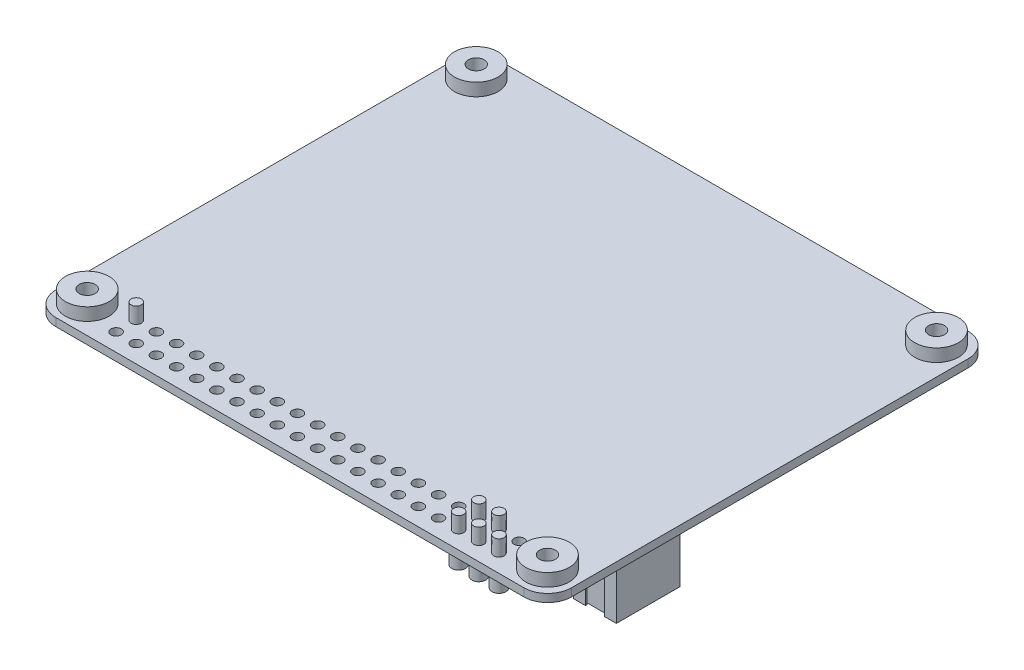
SolidWorks part; units mm, degrees
ref_plane "前视基准面" through (0, 0, 0) normal (0, 0, 1) x (1, 0, 0)
ref_plane "上视基准面" through (0, 0, 0) normal (0, 1, 0) x (1, 0, 0)
ref_plane "右视基准面" through (0, 0, 0) normal (1, 0, 0) x (0, 0, -1)
sketch "草图1" plane through (0, 0, 0) normal (0, 1, 0) x (1, 0, 0)
  line L1 (32.5, -28) -> (-32.5, -28)
  line L2 (32.5, -28) -> (32.5, 28)
  line L3 (32.5, 28) -> (-32.5, 28)
  line L4 (-32.5, -28) -> (-32.5, 28)
  line L5 (32.5, -28) -> (-32.5, 28) construction
  line L6 (32.5, 28) -> (-32.5, -28) construction
  point P0 (0, 0)
  dimension "D1" = 56
  dimension "D2" = 65
extrude "凸台-拉伸1" add sketch "草图1" along normal blind 1
fillet "圆角1" radius 3 4 edges at (32.5, 0.5, -28) (32.5, 0.5, 28) (-32.5, 0.5, 28) (-32.5, 0.5, -28)
sketch "草图2" plane through (0, 1, 0) normal (0, 1, 0) x (1, 0, 0)
  circle A0 centre (-29.0307, 24.5287) radius 2.75
  circle A1 centre (28.9808, 24.5287) radius 2.75
  circle A2 centre (-29.0307, -24.5065) radius 2.75
  circle A3 centre (28.9808, -24.5065) radius 2.75
  dimension "D1" = 5.5
extrude "凸台-拉伸2" add sketch "草图2" along normal blind 1.6
sketch "草图3" plane through (0, 2.6, 0) normal (0, 1, 0) x (1, 0, 0)
  circle A0 centre (-29.0307, 24.5287) radius 1
  circle A1 centre (28.9808, 24.5287) radius 1
  circle A2 centre (-29.0307, -24.5065) radius 1
  circle A3 centre (28.9808, -24.5065) radius 1
  dimension "D1" = 2
extrude "切除-拉伸1" cut sketch "草图3" against normal up to next
sketch "草图4" plane through (0, 0, 0) normal (0, -1, 0) x (1, 0, 0)
  line L0 (29.5, -28) -> (-29.5, -28) construction
  line L1 (25.5, -28) -> (16.5, -28)
  line L2 (25.5, -28) -> (25.5, -20.6)
  line L3 (25.5, -20.6) -> (16.5, -20.6)
  line L4 (16.5, -28) -> (16.5, -20.6)
  line L5 (32.5, 25) -> (32.5, -25) construction
  dimension "D1" = 7.4
  dimension "D2" = 9
  dimension "D3" = 7
extrude "凸台-拉伸3" add sketch "草图4" along normal blind 3.2
sketch "草图5" plane through (0, 0, -28) normal (0, 0, -1) x (-1, 0, 0)
  line L0 (-29.5, 0) -> (-25.5, 0) construction
  line L1 (-16.5, -3.2) -> (-25.5, -3.2)
  line L2 (-16.5, -3.2) -> (-16.5, 0)
  line L3 (-16.5, 0) -> (-25.5, 0)
  line L4 (-25.5, -3.2) -> (-25.5, 0)
  line L5 (-25.5, -3.2) -> (-25.5, 0) construction
extrude "凸台-拉伸4" add sketch "草图5" along normal blind 1
fillet "圆角3" radius 1 4 edges at (25.5, 0, -28.5) (25.5, -3.2, -24.8) (16.5, -3.2, -24.8) (16.5, 0, -28.5)
sketch "草图6" plane through (0, 0, 0) normal (0, -1, 0) x (1, 0, 0)
  line L0 (-32.5, -25) -> (-32.5, 25) construction
  circle A0 centre (-17.5, 0) radius 7
  dimension "D1" = 14
  dimension "D2" = 15
extrude "凸台-拉伸5" add sketch "草图6" along normal blind 2
sketch "草图8" plane through (0, 0, 0) normal (0, -1, 0) x (1, 0, 0)
  circle A0 centre (28.9808, 24.5065) radius 2
  circle A1 centre (28.9808, -24.5287) radius 2
  circle A2 centre (-29.0307, -24.5287) radius 2
  circle A3 centre (-29.0307, 24.5065) radius 2
  dimension "D1" = 4
extrude "凸台-拉伸6" add sketch "草图8" along normal blind 0.5
sketch "草图9" plane through (0, 0, 0) normal (0, 1, 0) x (1, 0, 0)
  circle A0 centre (-29.0307, 24.5287) radius 1
  circle A1 centre (28.9808, 24.5287) radius 1
  circle A2 centre (-29.0307, -24.5065) radius 1
  circle A3 centre (28.9808, -24.5065) radius 1
  circle A4 centre (28.9808, -24.5065) radius 2 construction
  circle A5 centre (28.9808, 24.5287) radius 2 construction
  circle A6 centre (-29.0307, -24.5065) radius 2 construction
  circle A7 centre (-29.0307, 24.5287) radius 2 construction
extrude "切除-拉伸2" cut sketch "草图9" against normal up to next
sketch "草图10" plane through (0, 0, -29) normal (0, 0, -1) x (-1, 0, 0)
  line L8 (-17.5, -0.2) -> (-24.5, -0.2)
  line L9 (-25.3, -1) -> (-25.3, -2.2)
  line L10 (-24.5, -3) -> (-17.5, -3)
  line L11 (-16.7, -2.2) -> (-16.7, -1)
  line L12 (-17.5, -0.2) -> (-24.5, -0.2)
  line L13 (-25.3, -1) -> (-25.3, -2.2)
  line L14 (-24.5, -3) -> (-17.5, -3)
  line L15 (-16.7, -2.2) -> (-16.7, -1)
  arc A8 (-24.5, -0.2) -> (-25.3, -1) centre (-24.5, -1) ccw
  arc A9 (-25.3, -2.2) -> (-24.5, -3) centre (-24.5, -2.2) ccw
  arc A10 (-17.5, -3) -> (-16.7, -2.2) centre (-17.5, -2.2) ccw
  arc A11 (-16.7, -1) -> (-17.5, -0.2) centre (-17.5, -1) ccw
  arc A12 (-24.5, -0.2) -> (-25.3, -1) centre (-24.5, -1) ccw
  arc A13 (-25.3, -2.2) -> (-24.5, -3) centre (-24.5, -2.2) ccw
  arc A14 (-17.5, -3) -> (-16.7, -2.2) centre (-17.5, -2.2) ccw
  arc A15 (-16.7, -1) -> (-17.5, -0.2) centre (-17.5, -1) ccw
  dimension "D1" = 0.2
extrude "切除-拉伸3" cut sketch "草图10" against normal blind 8
sketch "草图11" plane through (0, 0, 0) normal (0, -1, 0) x (1, 0, 0)
  line L0 (16.5, -28) -> (-29.5, -28) construction
  line L1 (6, -27.8) -> (10.5, -27.8)
  line L2 (6, -27.8) -> (6, -26.3)
  line L3 (6, -26.3) -> (10.5, -26.3)
  line L4 (10.5, -27.8) -> (10.5, -26.3)
  line L5 (16.5, -20.6) -> (16.5, -28) construction
  line L6 (-2.6793, -27.2) -> (-9.3793, -27.2)
  line L7 (-2.6793, -27.2) -> (-2.6793, -25)
  line L8 (-2.6793, -25) -> (-9.3793, -25)
  line L9 (-9.3793, -27.2) -> (-9.3793, -25)
  point P4 (0, 0)
  dimension "D1" = 6
  dimension "D2" = 4.5
  dimension "D3" = 6.7
  dimension "D4" = 0.8
  dimension "D5" = 2.2
  dimension "D6" = 1.5
  dimension "D7" = 8.7
  dimension "D8" = 0.2
extrude "凸台-拉伸7" add sketch "草图11" along normal blind 1.5
sketch "草图12" plane through (0, 0, 0) normal (0, -1, 0) x (1, 0, 0)
  line L0 (16.5, -28) -> (-29.5, -28) construction
  line L1 (-16.6, -28) -> (-23.9, -28)
  line L2 (-16.6, -28) -> (-16.6, -22.7)
  line L3 (-16.6, -22.7) -> (-23.9, -22.7)
  line L4 (-23.9, -28) -> (-23.9, -22.7)
  line L5 (-32.5, -25) -> (-32.5, 25) construction
  dimension "D1" = 7.3
  dimension "D2" = 8.6
  dimension "D3" = 5.3
extrude "凸台-拉伸8" add sketch "草图12" along normal blind 2.4
sketch "草图13" plane through (0, 0, -28) normal (0, 0, -1) x (-1, 0, 0)
  line L1 (23.9, -2.4) -> (16.6, -2.4)
  line L2 (23.9, -2.4) -> (23.9, 0)
  line L3 (23.9, 0) -> (16.6, 0)
  line L4 (16.6, -2.4) -> (16.6, 0)
extrude "凸台-拉伸9" add sketch "草图13" along normal up to surface (1 mm away) up to face at (21, -1.6, -29)
chamfer "倒角1" distance 0.4 angle 45 2 edges at (-16.6, -2.4, -25.85) (-23.9, -2.4, -25.85)
chamfer "倒角2" distance 1 angle 45 2 edges at (-16.6, 0, -28.5) (-23.9, 0, -28.5)
sketch "草图14" plane through (0, 0, -29) normal (0, 0, -1) x (-1, 0, 0)
  line L16 (22.8172, -0.2) -> (17.6828, -0.2)
  line L17 (17.6828, -0.2) -> (16.8, -1.0828)
  line L18 (16.8, -1.0828) -> (16.8, -1.9172)
  line L19 (16.8, -1.9172) -> (17.0828, -2.2)
  line L20 (17.0828, -2.2) -> (23.4172, -2.2)
  line L21 (23.4172, -2.2) -> (23.7, -1.9172)
  line L22 (23.7, -1.9172) -> (23.7, -1.0828)
  line L23 (23.7, -1.0828) -> (22.8172, -0.2)
  line L24 (22.8172, -0.2) -> (17.6828, -0.2)
  line L25 (17.6828, -0.2) -> (16.8, -1.0828)
  line L26 (16.8, -1.0828) -> (16.8, -1.9172)
  line L27 (16.8, -1.9172) -> (17.0828, -2.2)
  line L28 (17.0828, -2.2) -> (23.4172, -2.2)
  line L29 (23.4172, -2.2) -> (23.7, -1.9172)
  line L30 (23.7, -1.9172) -> (23.7, -1.0828)
  line L31 (23.7, -1.0828) -> (22.8172, -0.2)
  dimension "D1" = 0.2
extrude "切除-拉伸4" cut sketch "草图14" against normal blind 2.4
sketch "草图15" plane through (0, 0, -27.2) normal (0, 0, -1) x (-1, 0, 0)
  line L1 (6.6577, -1.3336) -> (5.7436, -1.3336)
  line L2 (6.6577, -1.3336) -> (6.6577, -0.2043)
  line L3 (6.6577, -0.2043) -> (5.7436, -0.2043)
  line L4 (5.7436, -1.3336) -> (5.7436, -0.2043)
extrude "凸台-拉伸10" add sketch "草图15" along normal blind 0.8
sketch "草图16" plane through (0, 0, -27.8) normal (0, 0, -1) x (-1, 0, 0)
  line L1 (-6.8432, -1.3088) -> (-8.9595, -1.3088)
  line L2 (-6.8432, -1.3088) -> (-6.8432, -0.1641)
  line L3 (-6.8432, -0.1641) -> (-8.9595, -0.1641)
  line L4 (-8.9595, -1.3088) -> (-8.9595, -0.1641)
extrude "凸台-拉伸11" add sketch "草图16" along normal blind 0.5
sketch "草图17" plane through (0, 0, -28) normal (0, 0, -1) x (-1, 0, 0)
  line L0 (23.9, -1) -> (23.9, 0)
  line L1 (23.9, 0) -> (22.9, 0)
  line L2 (22.9, 0) -> (23.9, -1)
  line L3 (16.6, 0) -> (17.6, 0)
  line L4 (17.6, 0) -> (16.6, -1)
  line L5 (16.6, -1) -> (16.6, 0) construction
  line L6 (16.6, -1) -> (16.6, 0)
extrude "切除-拉伸5" cut sketch "草图17" against normal up to surface (5.3 mm away) up to face at (-20.25, -1.4667, -22.7)
fillet "圆角4" radius 0.2 1 edges at (-17.5, -2, -7)
sketch "草图18" plane through (0, 0, 0) normal (0, -1, 0) x (1, 0, 0)
  line L0 (-29.5, 28) -> (29.5, 28) construction
  line L1 (27.1, 8.3) -> (20.1, 8.3)
  line L2 (27.1, 8.3) -> (27.1, 1.3)
  line L3 (27.1, 1.3) -> (20.1, 1.3)
  line L4 (20.1, 8.3) -> (20.1, 1.3)
  line L5 (27.1, -3.4) -> (20.1, -3.4)
  line L6 (27.1, -3.4) -> (27.1, -10.4)
  line L7 (27.1, -10.4) -> (20.1, -10.4)
  line L8 (20.1, -3.4) -> (20.1, -10.4)
  line L9 (32.5, 25) -> (32.5, -25) construction
  dimension "D1" = 7
  dimension "D2" = 19.7
  dimension "D3" = 4.7
  dimension "D4" = 5.4
extrude "凸台-拉伸12" add sketch "草图18" along normal blind 3
sketch "草图19" plane through (0, 0, 0) normal (0, -1, 0) x (1, 0, 0)
  line L0 (32.5, 25) -> (32.5, -25) construction
  line L1 (32, 18.85) -> (26.6, 18.85)
  line L2 (32, 18.85) -> (32, 10.85)
  line L3 (32, 10.85) -> (26.6, 10.85)
  line L4 (26.6, 18.85) -> (26.6, 10.85)
  line L5 (-29.5, 28) -> (29.5, 28) construction
  dimension "D1" = 8
  dimension "D2" = 5.4
  dimension "D3" = 0.5
  dimension "D4" = 9.15
extrude "凸台-拉伸13" add sketch "草图19" along normal blind 6.22
sketch "草图20" plane through (0, -6.22, 0) normal (0, -1, 0) x (1, 0, 0)
  line L0 (30.5, 18.85) -> (30.5, 18.65)
  line L1 (32, 18.85) -> (26.6, 18.85) construction
  line L2 (30.5, 18.65) -> (31.3599, 18.65)
  line L3 (31.3599, 18.65) -> (31.3599, 18.45)
  line L4 (31.3599, 18.45) -> (26.9378, 18.45)
  line L5 (26.9378, 18.45) -> (26.9378, 18.65)
  line L6 (26.9378, 18.65) -> (28.1, 18.65)
  line L7 (28.1, 18.65) -> (28.1, 18.85)
  line L8 (32, 18.85) -> (26.6, 18.85) construction
  line L9 (28.1, 18.85) -> (30.5, 18.85)
  line L10 (30.5, 10.85) -> (30.5, 11.05)
  line L11 (26.6, 10.85) -> (32, 10.85) construction
  line L12 (30.5, 11.05) -> (31.3599, 11.05)
  line L13 (31.3599, 11.05) -> (31.3599, 11.25)
  line L14 (31.3599, 11.25) -> (26.9378, 11.25)
  line L15 (26.9378, 11.25) -> (26.9378, 11.05)
  line L16 (26.9378, 11.05) -> (28.1, 11.05)
  line L17 (28.1, 11.05) -> (28.1, 10.85)
  line L18 (28.1, 10.85) -> (30.5, 10.85)
  line L19 (32, 10.85) -> (32, 18.85) construction
  line L20 (26.6, 18.85) -> (26.6, 10.85) construction
  dimension "D1" = 0.2
  dimension "D2" = 0.2
  dimension "D3" = 0.2
  dimension "D4" = 1.5
  dimension "D5" = 1.5
extrude "切除-拉伸6" cut sketch "草图20" against normal blind 6.22
sketch "草图21" plane through (0, -6.22, 0) normal (0, -1, 0) x (1, 0, 0)
  line L1 (31.3599, 18.0753) -> (26.9378, 18.0753)
  line L2 (31.3599, 18.0753) -> (31.3599, 11.6247)
  line L3 (31.3599, 11.6247) -> (26.9378, 11.6247)
  line L4 (26.9378, 18.0753) -> (26.9378, 11.6247)
  line L5 (31.3599, 18.0753) -> (26.9378, 11.6247) construction
  line L6 (31.3599, 11.6247) -> (26.9378, 18.0753) construction
  point P0 (29.1489, 14.85)
extrude "切除-拉伸7" cut sketch "草图21" against normal blind 5
sketch "草图22" plane through (0, -1.22, 0) normal (0, -1, 0) x (1, 0, 0)
  line L1 (29.5742, 16.0721) -> (29.0742, 16.0721)
  line L2 (29.5742, 16.0721) -> (29.5742, 15.5721)
  line L3 (29.5742, 15.5721) -> (29.0742, 15.5721)
  line L4 (29.0742, 16.0721) -> (29.0742, 15.5721)
  line L5 (29.5742, 16.0721) -> (29.0742, 15.5721) construction
  line L6 (29.5742, 15.5721) -> (29.0742, 16.0721) construction
  line L7 (29.5566, 14.331) -> (29.0566, 14.331)
  line L8 (29.5566, 14.331) -> (29.5566, 13.831)
  line L9 (29.5566, 13.831) -> (29.0566, 13.831)
  line L10 (29.0566, 14.331) -> (29.0566, 13.831)
  line L11 (29.5566, 14.331) -> (29.0566, 13.831) construction
  line L12 (29.5566, 13.831) -> (29.0566, 14.331) construction
  point P0 (29.3242, 15.8221)
  point P5 (29.3066, 14.081)
  dimension "D1" = 0.5
extrude "凸台-拉伸14" add sketch "草图22" along normal blind 5
chamfer "倒角3" distance 0.1 angle 45 8 edges at (29.3066, -6.22, 14.331) (29.5566, -6.22, 14.081) (29.3066, -6.22, 13.831) (29.0566, -6.22, 14.081) (29.3242, -6.22, 16.0721) (29.5742, -6.22, 15.8221) (29.3242, -6.22, 15.5721) (29.0742, -6.22, 15.8221)
sketch "草图23" plane through (0, 0, 0) normal (0, -1, 0) x (1, 0, 0)
  circle A0 centre (12.8757, -15.76) radius 3.3198
extrude "凸台-拉伸15" add sketch "草图23" along normal blind 1.5
sketch "草图24" plane through (0, 0, 0) normal (0, -1, 0) x (1, 0, 0)
  line L1 (18.7716, 11.9855) -> (16.6907, 11.9855)
  line L2 (18.7716, 11.9855) -> (18.7716, 7.4768)
  line L3 (18.7716, 7.4768) -> (16.6907, 7.4768)
  line L4 (16.6907, 11.9855) -> (16.6907, 7.4768)
  line L5 (18.7716, 11.9855) -> (16.6907, 7.4768) construction
  line L6 (18.7716, 7.4768) -> (16.6907, 11.9855) construction
  line L7 (18.7716, 5.3092) -> (16.6907, 5.3092)
  line L8 (18.7716, 5.3092) -> (18.7716, 0.974)
  line L9 (18.7716, 0.974) -> (16.6907, 0.974)
  line L10 (16.6907, 5.3092) -> (16.6907, 0.974)
  line L11 (18.7716, 5.3092) -> (16.6907, 0.974) construction
  line L12 (18.7716, 0.974) -> (16.6907, 5.3092) construction
  line L13 (15.6772, -1.762) -> (10.6483, -1.762)
  line L14 (15.6772, -1.762) -> (15.6772, -7.762)
  line L15 (15.6772, -7.762) -> (10.6483, -7.762)
  line L16 (10.6483, -1.762) -> (10.6483, -7.762)
  line L17 (15.6772, -1.762) -> (10.6483, -7.762) construction
  line L18 (15.6772, -7.762) -> (10.6483, -1.762) construction
  point P0 (17.7311, 9.7312)
  point P5 (17.7311, 3.1416)
  point P10 (13.1628, -4.762)
  dimension "D1" = 6
extrude "凸台-拉伸16" add sketch "草图24" along normal blind 1.5
sketch "草图25" plane through (0, 0, 0) normal (0, -1, 0) x (1, 0, 0)
  line L1 (15.1967, 7.9079) -> (11.1314, 7.9079)
  line L2 (15.1967, 7.9079) -> (15.1967, 3.8427)
  line L3 (15.1967, 3.8427) -> (11.1314, 3.8427)
  line L4 (11.1314, 7.9079) -> (11.1314, 3.8427)
  line L5 (15.1967, 7.9079) -> (11.1314, 3.8427) construction
  line L6 (15.1967, 3.8427) -> (11.1314, 7.9079) construction
  line L7 (21.5006, 15.4932) -> (19.7006, 15.4932)
  line L8 (21.5006, 15.4932) -> (21.5006, 14.4025)
  line L9 (21.5006, 14.4025) -> (19.7006, 14.4025)
  line L10 (19.7006, 15.4932) -> (19.7006, 14.4025)
  line L11 (21.5006, 15.4932) -> (19.7006, 14.4025) construction
  line L12 (21.5006, 14.4025) -> (19.7006, 15.4932) construction
  line L13 (21.5006, 13.6588) -> (19.7006, 13.6588)
  line L14 (21.5006, 13.6588) -> (21.5006, 12.5682)
  line L15 (21.5006, 12.5682) -> (19.7006, 12.5682)
  line L16 (19.7006, 13.6588) -> (19.7006, 12.5682)
  line L17 (21.5006, 13.6588) -> (19.7006, 12.5682) construction
  line L18 (21.5006, 12.5682) -> (19.7006, 13.6588) construction
  line L19 (21.5006, 11.8741) -> (19.7006, 11.8741)
  line L20 (21.5006, 11.8741) -> (21.5006, 10.7834)
  line L21 (21.5006, 10.7834) -> (19.7006, 10.7834)
  line L22 (19.7006, 11.8741) -> (19.7006, 10.7834)
  line L23 (21.5006, 11.8741) -> (19.7006, 10.7834) construction
  line L24 (21.5006, 10.7834) -> (19.7006, 11.8741) construction
  line L25 (18.7662, 14.8563) -> (17.6756, 14.8563)
  line L26 (18.7662, 14.8563) -> (18.7662, 13.0563)
  line L27 (18.7662, 13.0563) -> (17.6756, 13.0563)
  line L28 (17.6756, 14.8563) -> (17.6756, 13.0563)
  line L29 (18.7662, 14.8563) -> (17.6756, 13.0563) construction
  line L30 (18.7662, 13.0563) -> (17.6756, 14.8563) construction
  line L31 (16.9319, 14.8563) -> (15.8412, 14.8563)
  line L32 (16.9319, 14.8563) -> (16.9319, 13.0563)
  line L33 (16.9319, 13.0563) -> (15.8412, 13.0563)
  line L34 (15.8412, 14.8563) -> (15.8412, 13.0563)
  line L35 (16.9319, 14.8563) -> (15.8412, 13.0563) construction
  line L36 (16.9319, 13.0563) -> (15.8412, 14.8563) construction
  line L37 (15.0976, 14.8563) -> (14.0069, 14.8563)
  line L38 (15.0976, 14.8563) -> (15.0976, 13.0563)
  line L39 (15.0976, 13.0563) -> (14.0069, 13.0563)
  line L40 (14.0069, 14.8563) -> (14.0069, 13.0563)
  line L41 (15.0976, 14.8563) -> (14.0069, 13.0563) construction
  line L42 (15.0976, 13.0563) -> (14.0069, 14.8563) construction
  line L43 (13.2632, 14.8563) -> (12.1725, 14.8563)
  line L44 (13.2632, 14.8563) -> (13.2632, 13.0563)
  line L45 (13.2632, 13.0563) -> (12.1725, 13.0563)
  line L46 (12.1725, 14.8563) -> (12.1725, 13.0563)
  line L47 (13.2632, 14.8563) -> (12.1725, 13.0563) construction
  line L48 (13.2632, 13.0563) -> (12.1725, 14.8563) construction
  line L49 (11.3297, 14.8563) -> (10.2391, 14.8563)
  line L50 (11.3297, 14.8563) -> (11.3297, 13.0563)
  line L51 (11.3297, 13.0563) -> (10.2391, 13.0563)
  line L52 (10.2391, 14.8563) -> (10.2391, 13.0563)
  line L53 (11.3297, 14.8563) -> (10.2391, 13.0563) construction
  line L54 (11.3297, 13.0563) -> (10.2391, 14.8563) construction
  line L55 (9.2971, 14.8563) -> (8.2064, 14.8563)
  line L56 (9.2971, 14.8563) -> (9.2971, 13.0563)
  line L57 (9.2971, 13.0563) -> (8.2064, 13.0563)
  line L58 (8.2064, 14.8563) -> (8.2064, 13.0563)
  line L59 (9.2971, 14.8563) -> (8.2064, 13.0563) construction
  line L60 (9.2971, 13.0563) -> (8.2064, 14.8563) construction
  point P0 (13.1641, 5.8753)
  point P5 (20.6006, 14.9478)
  point P10 (20.6006, 13.1135)
  point P15 (20.6006, 11.3287)
  point P20 (18.2209, 13.9563)
  point P25 (16.3866, 13.9563)
  point P30 (14.5522, 13.9563)
  point P35 (12.7179, 13.9563)
  point P40 (10.7844, 13.9563)
  point P45 (8.7518, 13.9563)
  dimension "D1" = 1.8
extrude "凸台-拉伸17" add sketch "草图25" along normal blind 1
sketch "草图26" plane through (0, 0, 0) normal (0, -1, 0) x (1, 0, 0)
  circle A0 centre (24.13, 25.77) radius 0.65
  circle A40 centre (21.59, 25.77) radius 0.65
  circle A41 centre (19.05, 25.77) radius 0.65
  circle A42 centre (16.51, 25.77) radius 0.65
  circle A43 centre (13.97, 25.77) radius 0.65
  circle A44 centre (11.43, 25.77) radius 0.65
  circle A45 centre (8.89, 25.77) radius 0.65
  circle A46 centre (6.35, 25.77) radius 0.65
  circle A47 centre (3.81, 25.77) radius 0.65
  circle A48 centre (1.27, 25.77) radius 0.65
  circle A49 centre (-1.27, 25.77) radius 0.65
  circle A50 centre (-3.81, 25.77) radius 0.65
  circle A51 centre (-6.35, 25.77) radius 0.65
  circle A52 centre (-8.89, 25.77) radius 0.65
  circle A53 centre (-11.43, 25.77) radius 0.65
  circle A54 centre (-13.97, 25.77) radius 0.65
  circle A55 centre (-16.51, 25.77) radius 0.65
  circle A56 centre (-19.05, 25.77) radius 0.65
  circle A57 centre (-21.59, 25.77) radius 0.65
  circle A58 centre (-24.13, 25.77) radius 0.65
  circle A59 centre (21.59, 23.23) radius 0.65
  circle A60 centre (19.05, 23.23) radius 0.65
  circle A61 centre (16.51, 23.23) radius 0.65
  circle A62 centre (13.97, 23.23) radius 0.65
  circle A63 centre (11.43, 23.23) radius 0.65
  circle A64 centre (8.89, 23.23) radius 0.65
  circle A65 centre (6.35, 23.23) radius 0.65
  circle A66 centre (3.81, 23.23) radius 0.65
  circle A67 centre (1.27, 23.23) radius 0.65
  circle A68 centre (-1.27, 23.23) radius 0.65
  circle A69 centre (-3.81, 23.23) radius 0.65
  circle A70 centre (-6.35, 23.23) radius 0.65
  circle A71 centre (-8.89, 23.23) radius 0.65
  circle A72 centre (-11.43, 23.23) radius 0.65
  circle A73 centre (-13.97, 23.23) radius 0.65
  circle A74 centre (-16.51, 23.23) radius 0.65
  circle A75 centre (-19.05, 23.23) radius 0.65
  circle A76 centre (-21.59, 23.23) radius 0.65
  circle A77 centre (-24.13, 23.23) radius 0.65
  circle A78 centre (24.13, 23.23) radius 0.65
  dimension "D1" = 1.3
  dimension "D2" = 20
  dimension "D3" = 2
extrude "切除-拉伸8" cut sketch "草图26" against normal up to surface (1 mm away) up to face at (28.9808, 1, 27.2565)
sketch "草图27" plane through (0, 0, 0) normal (0, -1, 0) x (1, 0, 0)
  circle A0 centre (24.13, 25.77) radius 1.15
  circle A1 centre (21.59, 25.77) radius 1.15
  circle A2 centre (21.59, 23.23) radius 1.15
  circle A3 centre (19.05, 25.77) radius 1.15
  circle A4 centre (19.05, 23.23) radius 1.15
  circle A5 centre (-24.13, 23.23) radius 1.15
  circle A6 centre (21.59, 25.77) radius 0.65 construction
  dimension "D1" = 2.3
extrude "凸台-拉伸18" add sketch "草图27" along normal blind 0.8
sketch "草图28" plane through (0, -0.8, 0) normal (0, -1, 0) x (-1, 0, 0)
  circle A0 centre (-24.13, -25.77) radius 0.875
  circle A1 centre (-21.59, -25.77) radius 0.875
  circle A2 centre (-19.05, -23.23) radius 0.875
  circle A3 centre (-21.59, -23.23) radius 0.875
  circle A4 centre (-19.05, -25.77) radius 0.875
  circle A5 centre (24.13, -23.23) radius 0.875
  dimension "D1" = 1.75
extrude "凸台-拉伸19" add sketch "草图28" along normal blind 2
sketch "草图29" plane through (0, 0, 0) normal (0, 1, 0) x (1, 0, 0)
  circle A0 centre (19.05, -23.23) radius 0.65 construction
  circle A1 centre (19.05, -25.77) radius 0.65 construction
  circle A2 centre (21.59, -23.23) radius 0.65 construction
  circle A4 centre (24.13, -25.77) radius 0.65 construction
  circle A5 centre (-24.13, -23.23) radius 0.65 construction
  circle A6 centre (19.05, -23.23) radius 0.65
  circle A7 centre (19.05, -25.77) radius 0.65
  circle A8 centre (21.59, -23.23) radius 0.65
  circle A9 centre (21.59, -25.77) radius 0.65
  circle A10 centre (24.13, -25.77) radius 0.65
  circle A11 centre (-24.13, -23.23) radius 0.65
  circle A12 centre (21.59, -25.77) radius 0.65 construction
extrude "凸台-拉伸20" add sketch "草图29" along normal blind 3
sketch "草图30" plane through (0, 0, 0) normal (0, -1, 0) x (1, 0, 0)
  line L1 (-0.3871, -24.7121) -> (2.6129, -24.7121)
  line L2 (-0.3871, -24.7121) -> (-0.3871, -27.7121)
  line L3 (-0.3871, -27.7121) -> (2.6129, -27.7121)
  line L4 (2.6129, -24.7121) -> (2.6129, -27.7121)
  line L5 (-0.3871, -24.7121) -> (2.6129, -27.7121) construction
  line L6 (-0.3871, -27.7121) -> (2.6129, -24.7121) construction
  point P0 (1.1129, -26.2121)
  dimension "D1" = 3
  dimension "D2" = 3
extrude "凸台-拉伸21" add sketch "草图30" along normal blind 1
sketch "草图31" plane through (0, -1, 0) normal (0, -1, 0) x (1, 0, 0)
  line L0 (2.6129, -27.7121) -> (2.6129, -24.7121) construction
  line L1 (-0.3871, -27.7121) -> (2.6129, -27.7121) construction
  circle A0 centre (1.1129, -26.2121) radius 1
  point P5 (2.6129, -26.2121)
  point P8 (1.1129, -27.7121)
  dimension "D1" = 2
extrude "凸台-拉伸22" add sketch "草图31" along normal blind 0.6
chamfer "倒角4" distance 0.4 angle 45 4 edges at (2.6129, -0.5, -24.7121) (-0.3871, -0.5, -24.7121) (2.6129, -0.5, -27.7121) (-0.3871, -0.5, -27.7121)
